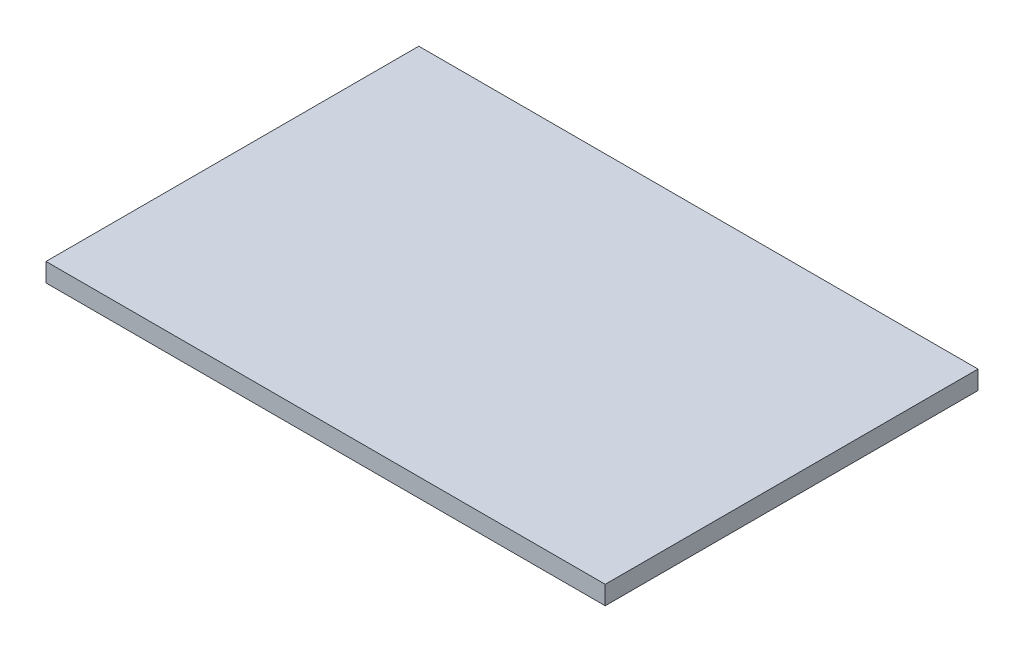
SolidWorks part; units mm, degrees
material "Acrylic (Medium-high impact)"
ref_plane "Front Plane" through (0, 0, 0) normal (0, 0, 1) x (1, 0, 0)
ref_plane "Top Plane" through (0, 0, 0) normal (0, 1, 0) x (1, 0, 0)
ref_plane "Right Plane" through (0, 0, 0) normal (1, 0, 0) x (0, 0, -1)
sketch "Sketch1" plane through (0, 0, 0) normal (0, 1, 0) x (1, 0, 0)
  line L1 (-29.3183, -4.7578) -> (46.8817, -4.7578)
  line L2 (-29.3183, -4.7578) -> (-29.3183, 46.0422)
  line L3 (-29.3183, 46.0422) -> (46.8817, 46.0422)
  line L4 (46.8817, -4.7578) -> (46.8817, 46.0422)
  dimension "D1" = 76.2
  dimension "D2" = 50.8
extrude "Extrude1" add sketch "Sketch1" along normal blind 2.54
